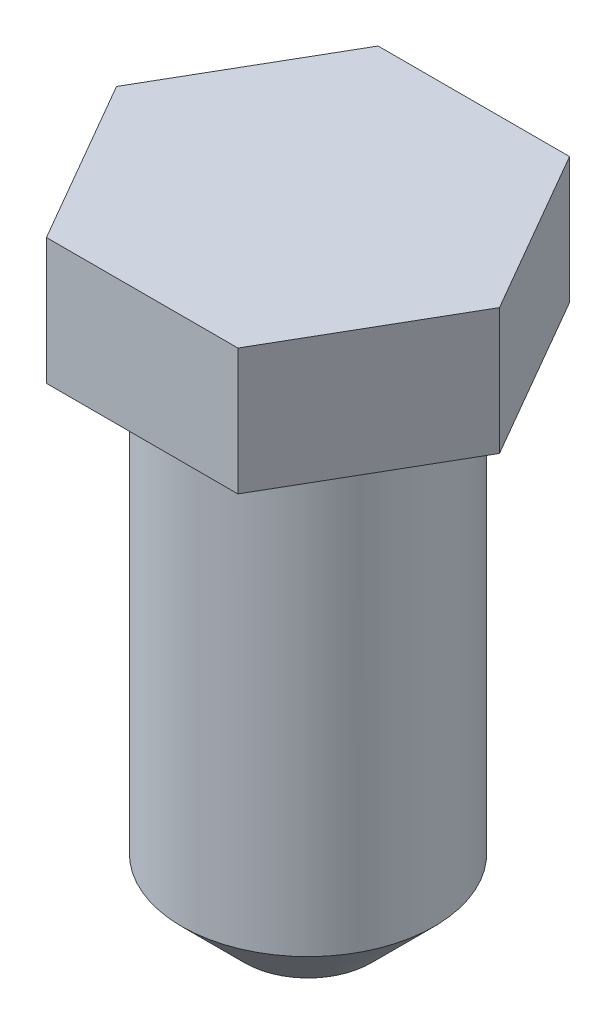
SolidWorks part; units mm, degrees
ref_plane "Front Plane" through (0, 0, 0) normal (0, 0, 1) x (1, 0, 0)
ref_plane "Top Plane" through (0, 0, 0) normal (0, 1, 0) x (1, 0, 0)
ref_plane "Right Plane" through (0, 0, 0) normal (1, 0, 0) x (0, 0, -1)
sketch "Sketch1" plane through (0, 0, 0) normal (0, 1, 0) x (1, 0, 0)
  line L1 (19.2474, 0) -> (9.6237, 16.6687)
  line L2 (9.6237, 16.6687) -> (-9.6237, 16.6688)
  line L3 (-9.6237, 16.6688) -> (-19.2474, 0)
  line L4 (-19.2474, 0) -> (-9.6237, -16.6687)
  line L5 (-9.6237, -16.6687) -> (9.6237, -16.6687)
  line L6 (9.6237, -16.6687) -> (19.2474, 0)
  circle A0 centre (0, 0) radius 16.6687 construction
  dimension "D1" = 33.3375
  dimension "D2" = 16.6688
extrude "Boss-Extrude1" add sketch "Sketch1" along normal blind 12.7
sketch "Sketch2" plane through (0, 0, 0) normal (0, -1, 0) x (1, 0, 0)
  circle A0 centre (0, 0) radius 12.7
extrude "Boss-Extrude2" add sketch "Sketch2" along normal blind 44.45
sketch "Sketch3" plane through (0, -44.45, 0) normal (0, -1, 0) x (-1, 0, 0)
  circle A0 centre (0, 0) radius 12.7
extrude "Boss-Extrude3" add sketch "Sketch3" along normal blind 6.35
chamfer "Chamfer1" distance 6.35 angle 45 1 edges at (0, -50.8, -12.7)
